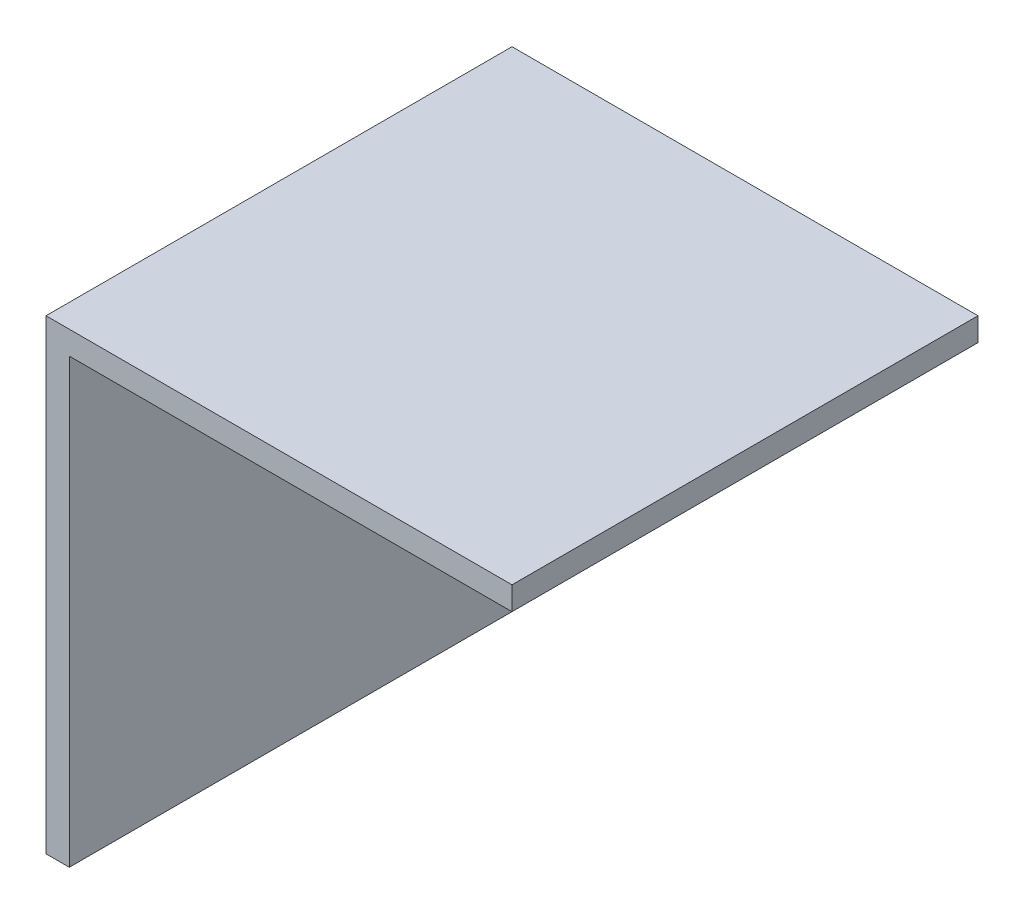
SolidWorks part; units mm, degrees
ref_plane "Front Plane" through (0, 0, 0) normal (0, 0, 1) x (1, 0, 0)
ref_plane "Top Plane" through (0, 0, 0) normal (0, 1, 0) x (1, 0, 0)
ref_plane "Right Plane" through (0, 0, 0) normal (1, 0, 0) x (0, 0, -1)
sketch "Sketch1" plane through (0, 0, 0) normal (0, 0, 1) x (1, 0, 0)
  line L0 (0, 0) -> (0, 50.8)
  line L1 (0, 50.8) -> (50.8, 50.8)
  line L2 (2.54, 0) -> (2.54, 48.26)
  line L3 (2.54, 48.26) -> (50.8, 48.26)
  line L4 (0, 0) -> (2.54, 0)
  line L5 (50.8, 48.26) -> (50.8, 50.8)
  dimension "D1" = 50.8
  dimension "D2" = 2.54
extrude "Boss-Extrude1" add sketch "Sketch1" along normal blind 50.8
